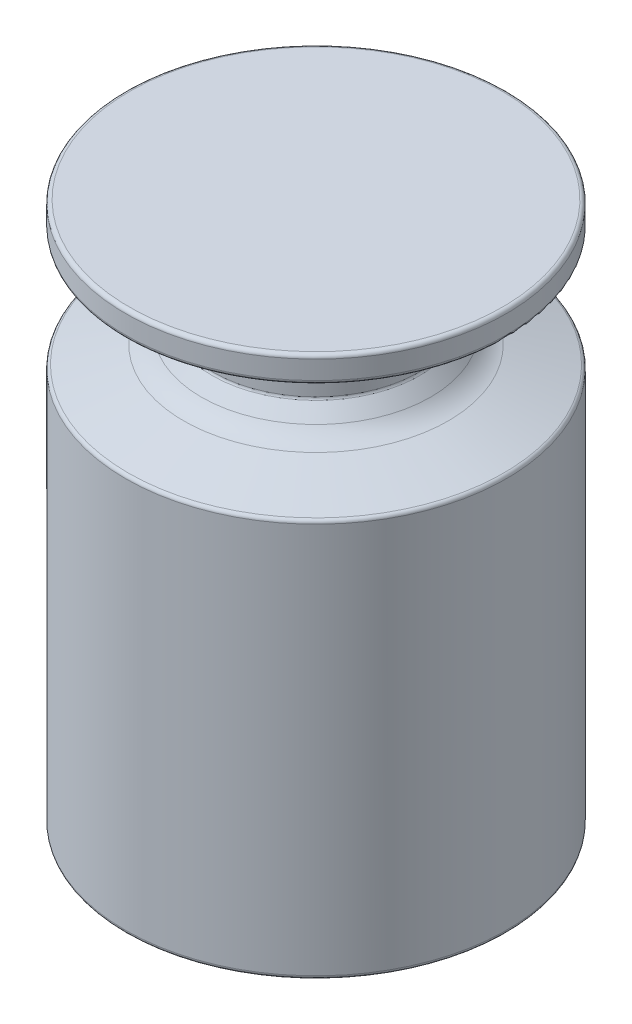
SolidWorks part; units mm, degrees
ref_plane "Front Plane" through (0, 0, 0) normal (0, 0, 1) x (1, 0, 0)
ref_plane "Top Plane" through (0, 0, 0) normal (0, 1, 0) x (1, 0, 0)
ref_plane "Right Plane" through (0, 0, 0) normal (1, 0, 0) x (0, 0, -1)
sketch "Sketch1" plane through (0, 0, 0) normal (0, 0, 1) x (1, 0, 0)
  line L0 (0, 67.0923) -> (0, -67.0923) construction
  line L1 (-25, 35.55) -> (25, 35.55) construction
  line L2 (-25, 35.55) -> (-25, -35.55) construction
  line L3 (-25, -35.55) -> (25, -35.55) construction
  line L4 (25, 35.55) -> (25, -35.55) construction
  line L5 (-25, 35.55) -> (25, -35.55) construction
  line L6 (-25, -35.55) -> (25, 35.55) construction
  line L7 (13.5, 24.45) -> (25, 24.45) construction
  line L8 (-25, 16.65) -> (25, 16.65) construction
  line L9 (-25, 16.65) -> (-25, -35.55) construction
  line L10 (-25, -35.55) -> (25, -35.55) construction
  line L11 (25, 16.65) -> (25, -35.55) construction
  line L12 (-25, 35.55) -> (25, 35.55) construction
  line L13 (-25, 35.55) -> (-25, 32.25) construction
  line L14 (-25, 32.25) -> (25, 32.25) construction
  line L15 (25, 35.55) -> (25, 32.25) construction
  line L16 (0, 32.25) -> (13.5, 32.25) construction
  line L17 (0, 32.25) -> (0, 16.65) construction
  line L18 (0, 16.65) -> (13.5, 16.65) construction
  line L19 (13.5, 32.25) -> (13.5, 16.65) construction
  line L20 (25, 32.25) -> (16, 29.4123)
  line L21 (13.5, 22.45) -> (13.5, 26.45)
  line L22 (13.5, 26.45) -> (16, 29.4123)
  line L23 (13.5, 22.45) -> (16, 19.4877)
  line L24 (25, 16.65) -> (16, 19.4877)
  line L25 (0, 35.55) -> (25, 35.55)
  line L26 (25, 35.55) -> (25, 32.25)
  line L27 (25, 16.65) -> (25, -35.55)
  line L28 (25, -35.55) -> (0, -35.55)
  line L29 (0, 35.55) -> (0, -35.55)
  point P0 (0, 0)
  point P9 (0, 0)
  point P22 (13.5, 24.45)
  dimension "D1" = 50
  dimension "D2" = 71.1
  dimension "D3" = 52.2
  dimension "D4" = 3.3
  dimension "D5" = 15.6
  dimension "D6" = 11.5
  dimension "D7" = 4
  dimension "D8" = 17.5
  dimension "D9" = 9
revolve "Revolve1" add sketch "Sketch1" angle 360 about L0
fillet "Fillet1" radius 5 2 edges at (0, 19.4877, 16) (0, 29.4123, 16)
fillet "Fillet2" radius 0.5 6 edges at (0, 26.45, 13.5) (0, 22.45, 13.5) (0, -35.55, 25) (0, 16.65, 25) (0, 32.25, 25) (0, 35.55, 25)
ref_plane "Plane1" through (24.65, 0, 0) normal (1, 0, 0) x (0, 0, -1)
